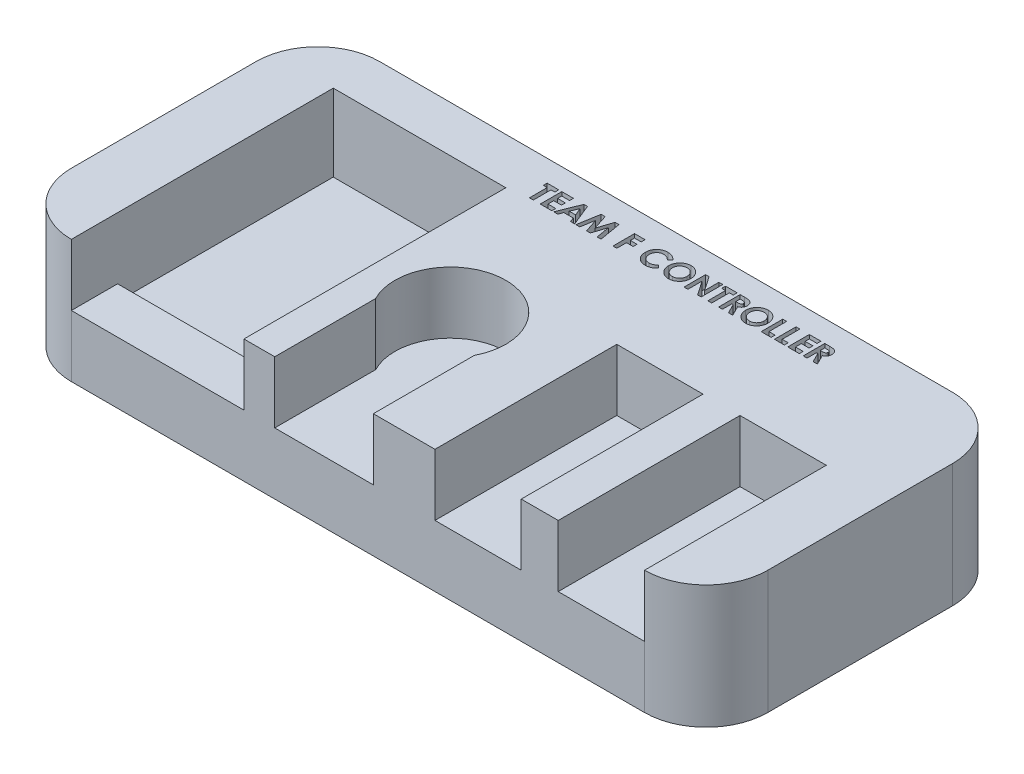
SolidWorks part; units mm, degrees
ref_plane "Front Plane" through (0, 0, 0) normal (0, 0, 1) x (1, 0, 0)
ref_plane "Top Plane" through (0, 0, 0) normal (0, 1, 0) x (1, 0, 0)
ref_plane "Right Plane" through (0, 0, 0) normal (1, 0, 0) x (0, 0, -1)
sketch "Sketch1" plane through (0, 0, 0) normal (0, 1, 0) x (1, 0, 0)
  line L1 (-56.5, 25) -> (56.5, 25)
  line L2 (-56.5, 25) -> (-56.5, -25)
  line L3 (-56.5, -25) -> (56.5, -25)
  line L4 (56.5, 25) -> (56.5, -25)
  line L5 (-56.5, 25) -> (56.5, -25) construction
  line L6 (-56.5, -25) -> (56.5, 25) construction
  point P0 (0, 0)
  dimension "D1" = 113
  dimension "D2" = 50
extrude "Boss-Extrude1" add sketch "Sketch1" along normal blind 20
sketch "Sketch2" plane through (0, 20, 0) normal (0, 1, 0) x (1, 0, 0)
  line L0 (-56.5, 25) -> (-56.5, -25) construction
  line L1 (-46.5, 17.5) -> (-18.5, 17.5)
  line L2 (-46.5, 17.5) -> (-46.5, -17.5)
  line L3 (-46.5, -17.5) -> (-18.5, -17.5)
  line L4 (-18.5, 17.5) -> (-18.5, -17.5)
  line L5 (-46.5, 17.5) -> (-18.5, -17.5) construction
  line L6 (-46.5, -17.5) -> (-18.5, 17.5) construction
  line L13 (56.5, 25) -> (-56.5, 25) construction
  point P0 (-32.5, 0)
  dimension "D4" = 10
  dimension "D5" = 28
  dimension "D6" = 35
  dimension "D7" = 25
extrude "Cut-Extrude2" cut sketch "Sketch2" against normal blind 12.5
sketch "Sketch3" plane through (0, 20, 0) normal (0, 1, 0) x (1, 0, 0)
  line L0 (-13.5, -8.6231) -> (-13.5, -17.5)
  line L1 (-13.5, -17.5) -> (2.5, -17.5)
  line L2 (2.5, -8.6231) -> (2.5, -17.5)
  line L3 (-13.5, -8.6231) -> (2.5, -17.5) construction
  line L4 (-13.5, -17.5) -> (2.5, -8.6231) construction
  line L9 (-18.5, -17.5) -> (-18.5, 17.5) construction
  line L10 (-46.5, -17.5) -> (-18.5, -17.5) construction
  arc A0 (-13.5, -8.6231) -> (2.5, -8.6231) centre (-5.5, -4.5) cw
  point P0 (-5.5, -13.0616)
  dimension "D3" = 9
  dimension "D1" = 5
  dimension "D2" = 16
  dimension "D4" = 13
extrude "Cut-Extrude3" cut sketch "Sketch3" against normal blind 10
sketch "Sketch4" plane through (0, 20, 0) normal (0, 1, 0) x (1, 0, 0)
  line L0 (26.5, -17.5) -> (12.5, -17.5)
  line L1 (26.5, -17.5) -> (26.5, 4.5)
  line L2 (26.5, 4.5) -> (12.5, 4.5)
  line L3 (12.5, -17.5) -> (12.5, 4.5)
  line L4 (26.5, -17.5) -> (12.5, 4.5) construction
  line L5 (26.5, 4.5) -> (12.5, -17.5) construction
  line L6 (46.5, -17.5) -> (32.5, -17.5)
  line L7 (46.5, -17.5) -> (46.5, 4.5)
  line L8 (46.5, 4.5) -> (32.5, 4.5)
  line L9 (32.5, -17.5) -> (32.5, 4.5)
  line L10 (46.5, -17.5) -> (32.5, 4.5) construction
  line L11 (46.5, 4.5) -> (32.5, -17.5) construction
  line L13 (2.5, -17.5) -> (2.5, -8.6231) construction
  line L14 (-13.5, -17.5) -> (2.5, -17.5) construction
  point P0 (19.5, -6.5)
  point P5 (39.5, -6.5)
  dimension "D1" = 14
  dimension "D2" = 22
  dimension "D3" = 14
  dimension "D5" = 10
  dimension "D6" = 6
extrude "Cut-Extrude4" cut sketch "Sketch4" against normal blind 10
sketch "Sketch5" plane through (0, 20, 0) normal (0, 1, 0) x (1, 0, 0)
  line L0 (-16.5, 18) -> (33.5, 18) construction
  line L1 (-56.5, 25) -> (-56.5, -25) construction
  line L2 (56.5, 25) -> (-56.5, 25) construction
  text T0 "<b>TEAM F CONTROLLER</b>"
  dimension "D1" = 50
  dimension "D2" = 40
  dimension "D3" = 7
extrude "Cut-Extrude5" cut sketch "Sketch5" against normal blind 2
sketch "Sketch6" plane through (0, 0, 17.5) normal (0, 0, -1) x (-1, 0, 0)
  line L1 (-46.5, 10) -> (-32.5, 10)
  line L2 (-46.5, 10) -> (-46.5, 20)
  line L3 (-46.5, 20) -> (-32.5, 20)
  line L4 (-32.5, 10) -> (-32.5, 20)
  line L5 (-46.5, 10) -> (-46.5, 20) construction
  line L6 (-26.5, 10) -> (-12.5, 10)
  line L7 (-26.5, 10) -> (-26.5, 20)
  line L8 (-26.5, 20) -> (-12.5, 20)
  line L9 (-12.5, 10) -> (-12.5, 20)
  line L10 (56.5, 20) -> (-56.5, 20) construction
  line L11 (-2.5, 10) -> (13.5, 10)
  line L12 (-2.5, 10) -> (-2.5, 20)
  line L13 (-2.5, 20) -> (13.5, 20)
  line L14 (13.5, 10) -> (13.5, 20)
  line L15 (46.5, 7.5) -> (46.5, 20) construction
  line L16 (18.5, 10) -> (46.5, 10)
  line L17 (18.5, 10) -> (18.5, 20)
  line L18 (18.5, 20) -> (46.5, 20)
  line L19 (46.5, 10) -> (46.5, 20)
  dimension "D1" = 5
  dimension "D3" = 6
  dimension "D4" = 10
  dimension "D5" = 14
  dimension "D6" = 10
  dimension "D8" = 14
  dimension "D9" = 16
extrude "Cut-Extrude6" cut sketch "Sketch6" against normal blind 10
fillet "Fillet1" radius 10 4 edges at (-56.5, 10, 25) (56.5, 10, 25) (56.5, 10, -25) (-56.5, 10, -25)
